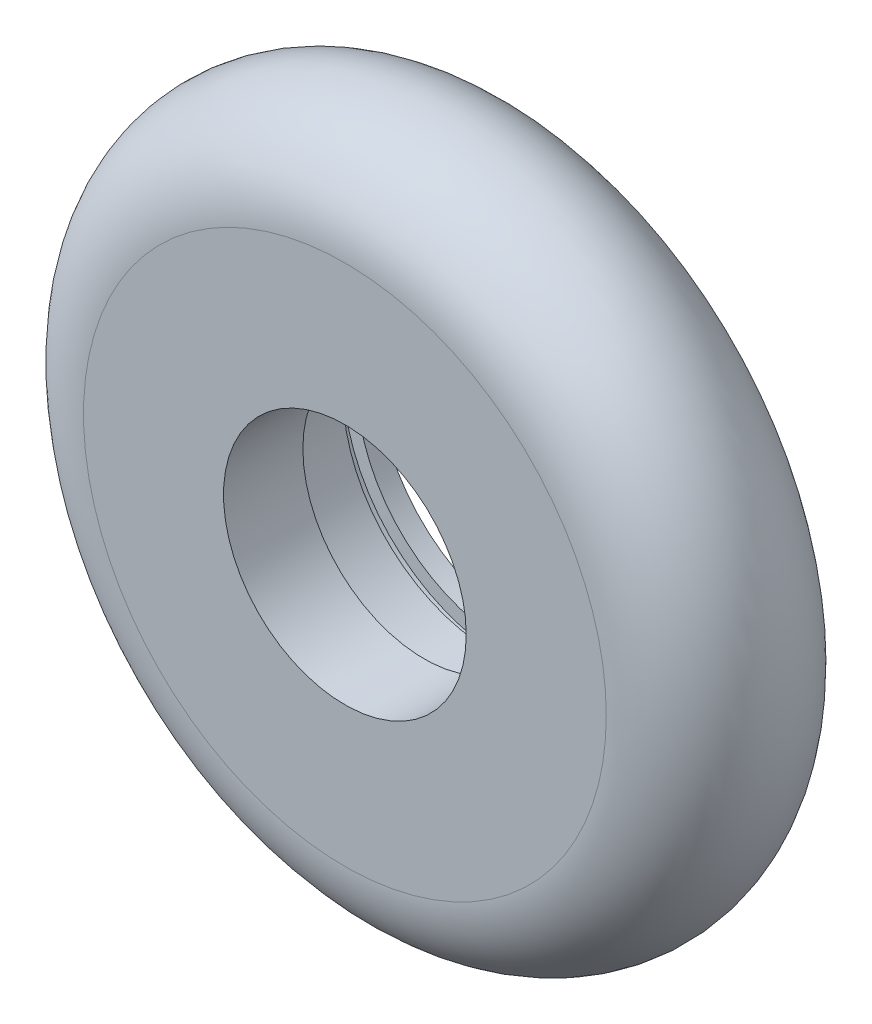
SolidWorks part; units mm, degrees
material "45"
ref_plane "前视基准面" through (0, 0, 0) normal (0, 0, 1) x (1, 0, 0)
ref_plane "上视基准面" through (0, 0, 0) normal (0, 1, 0) x (1, 0, 0)
ref_plane "右视基准面" through (0, 0, 0) normal (1, 0, 0) x (0, 0, -1)
sketch "草图1" plane through (0, 0, 0) normal (0, 1, 0) x (1, 0, 0)
  line L0 (0, 0) -> (0, 166.4181) construction
  line L1 (13, 0) -> (28, 0)
  line L2 (28, 19.5) -> (13, 19.5)
  line L4 (13, 19.5) -> (13, 0)
  arc A0 (28, 0) -> (28, 19.5) centre (28, 9.75) ccw
  dimension "D1" = 56
  dimension "D2" = 19.5
  dimension "D3" = 19.5
  dimension "D4" = 13
  dimension "D5" = 0
revolve "旋转1" add sketch "草图1" angle 360 about L0
ref_plane "基准面1" through (0, 0, -10) normal (0, 0, 1) x (1, 0, 0)
sketch "草图2" plane through (0, 0, -19.5) normal (0, 0, -1) x (-1, 0, 0)
  circle A0 centre (0, 0) radius 16
  dimension "D1" = 32
extrude "切除-拉伸1" cut sketch "草图2" against normal blind 11
sketch "草图3" plane through (0, 0, 0) normal (0, 1, 0) x (1, 0, 0)
  line L0 (0, 0) -> (0, 19.5) construction
  line L1 (16, 19.5) -> (-16, 19.5) construction
  line L4 (16, 17.3) -> (17.5, 17.3)
  line L5 (17.5, 15.8) -> (16, 15.8)
  line L6 (16, 17.3) -> (16, 15.8)
  line L7 (16, 8.5) -> (-16, 8.5) construction
  line L8 (17.5, 17.3) -> (17.5, 15.8)
  line L9 (17.5, 15.8) -> (17.4527, 11.2709)
  dimension "D1" = 16
  dimension "D2" = 7.3
  dimension "D3" = 1.5
  dimension "D4" = 17.5
revolve "切除-旋转1" cut sketch "草图3" angle 360 about L0
ref_plane "基准面2" through (0, 0, -9.25) normal (0, 0, 1) x (1, 0, 0)
sketch "草图4" plane through (0, 0, -9.25) normal (0, 0, 1) x (1, 0, 0)
  point P0 (0, 0)
